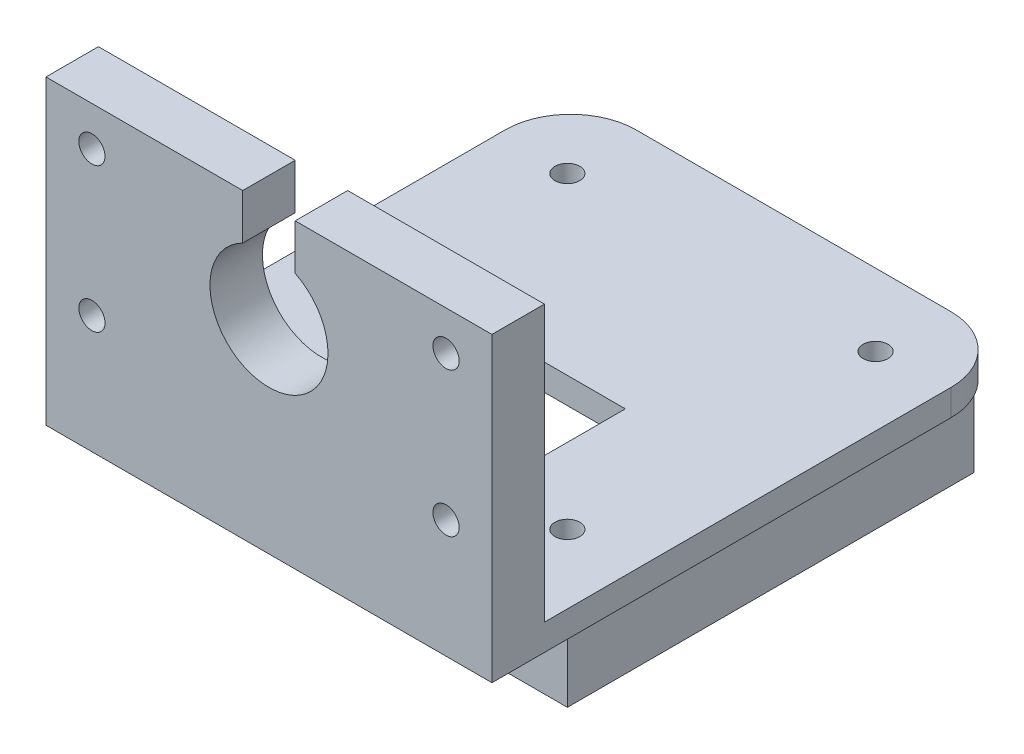
SolidWorks part; units mm, degrees
ref_plane "Спереди" through (0, 0, 0) normal (0, 0, 1) x (1, 0, 0)
ref_plane "Сверху" through (0, 0, 0) normal (0, 1, 0) x (1, 0, 0)
ref_plane "Справа" through (0, 0, 0) normal (1, 0, 0) x (0, 0, -1)
sketch "Эскиз1" plane through (0, 0, 0) normal (0, 0, 1) x (1, 0, 0)
  line L0 (0, 11.5) -> (0, 8.5) construction
  line L1 (-17, -11.5) -> (17, -11.5)
  line L2 (-17, -11.5) -> (-17, 11.5)
  line L4 (17, -11.5) -> (17, 11.5)
  line L5 (-17, -11.5) -> (17, 11.5) construction
  line L6 (-17, 11.5) -> (17, -11.5) construction
  line L7 (-13.5, 8.5) -> (13.5, 8.5) construction
  line L8 (-13.5, 8.5) -> (-13.5, -2.5) construction
  line L9 (-13.5, -2.5) -> (13.5, -2.5) construction
  line L10 (13.5, -2.5) -> (13.5, -9.5) construction
  line L11 (-17, -9.5) -> (17, -9.5) construction
  line L12 (0, -9.5) -> (0, -0.5) construction
  line L13 (-2, 11.5) -> (2, 11.5) construction
  line L14 (-2, 11.5) -> (-2, 8.0311)
  line L15 (2, 11.5) -> (2, 8.0311)
  line L16 (2, 11.5) -> (17, 11.5)
  line L17 (-2, 11.5) -> (-17, 11.5)
  circle A0 centre (-13.5, 8.5) radius 1
  circle A1 centre (13.5, 8.5) radius 1
  circle A2 centre (-13.5, -2.5) radius 1
  circle A3 centre (13.5, -2.5) radius 1
  arc A5 (-2, 8.0311) -> (2, 8.0311) centre (0, 4) ccw
  point P0 (0, 0)
  point P11 (0, 8.5)
  point P27 (0, 11.5)
extrude "Бобышка-Вытянуть1" add sketch "Эскиз1" along normal blind 4
sketch "Эскиз2" plane through (0, 0, 0) normal (0, 0, -1) x (-1, 0, 0)
  line L1 (-17, -9.5) -> (17, -9.5)
  line L2 (-17, -9.5) -> (-17, -11.5)
  line L3 (-17, -11.5) -> (17, -11.5)
  line L4 (17, -9.5) -> (17, -11.5)
  line L5 (-17, -9.5) -> (17, -11.5) construction
  line L6 (-17, -11.5) -> (17, -9.5) construction
  point P4 (0, -10.5)
extrude "Бобышка-Вытянуть2" add sketch "Эскиз2" along normal blind 36
sketch "Эскиз3" plane through (0, -11.5, 0) normal (0, -1, 0) x (1, 0, 0)
  line L1 (0, -18.75) -> (0, 0) construction
  line L3 (6, -17.1698) -> (-6, -17.1698)
  line L5 (6, -17.1698) -> (6, -3)
  line L6 (0, -18.75) -> (0, -36) construction
  line L7 (6, -3) -> (-6, -3)
  line L8 (-11.75, -7) -> (11.75, -7) construction
  line L9 (-11.75, -7) -> (-11.75, -30.5) construction
  line L10 (-11.75, -30.5) -> (11.75, -30.5) construction
  line L11 (11.75, -7) -> (11.75, -30.5) construction
  line L12 (-11.75, -7) -> (11.75, -30.5) construction
  line L13 (-11.75, -30.5) -> (11.75, -7) construction
  line L14 (-6, -3) -> (-6, -17.1698)
  line L15 (0, -3) -> (0, 0) construction
  line L16 (-17, 0) -> (17, 0) construction
  line L17 (17, -36) -> (-17, -36) construction
  line L18 (0, -18.75) -> (-17, -18.75) construction
  line L19 (-17, 4) -> (-17, -36) construction
  line L20 (0, -18.75) -> (17, -18.75) construction
  line L21 (17, 4) -> (17, -36) construction
  circle A0 centre (11.75, -7) radius 0.95
  circle A1 centre (11.75, -30.5) radius 0.95
  circle A2 centre (-11.75, -30.5) radius 0.95
  circle A3 centre (-11.75, -7) radius 0.95
  point P5 (0, 0)
  point P10 (0, -18.75)
  point P12 (0, -18.75)
extrude "Вырез-Вытянуть1" cut sketch "Эскиз3" against normal blind 3
sketch "Эскиз4" plane through (0, -11.5, 0) normal (0, -1, 0) x (1, 0, 0)
  circle A0 centre (11.75, -7) radius 2.2
  circle A1 centre (11.75, -30.5) radius 2.2
  circle A2 centre (-11.75, -7) radius 2.2
  circle A3 centre (-11.75, -30.5) radius 2.2
  circle A4 centre (11.75, -7) radius 0.95
  circle A5 centre (11.75, -30.5) radius 0.95
  circle A6 centre (-11.75, -30.5) radius 0.95
  circle A7 centre (-11.75, -7) radius 0.95
extrude "Бобышка-Вытянуть3" add sketch "Эскиз4" along normal blind 2
fillet "Скругление1" radius 5 2 edges at (17, -10.5, -36) (-17, -10.5, -36)
sketch "Эскиз5" plane through (0, -11.5, 0) normal (0, -1, 0) x (1, 0, 0)
  line L0 (-11.75, -7) -> (11.75, -30.5) construction
  line L1 (11.75, -7) -> (-11.75, -30.5) construction
  line L2 (-6, -3.25) -> (6, -3.25) construction
  line L3 (-14, -32.75) -> (14, -32.75)
  line L4 (-14, -32.75) -> (-14, -4.75)
  line L6 (14, -32.75) -> (14, -4.75)
  line L7 (-14, -32.75) -> (14, -4.75) construction
  line L8 (-14, -4.75) -> (14, -32.75) construction
  line L10 (-15.5, -3.25) -> (-15.5, -34.25)
  line L11 (-15.5, -34.25) -> (15.5, -34.25)
  line L12 (15.5, -3.25) -> (15.5, -34.25)
  line L13 (-15.5, -3.25) -> (15.5, -34.25) construction
  line L14 (-15.5, -34.25) -> (15.5, -3.25) construction
  line L15 (-15.5, -4.75) -> (-15.5, -34.25)
  line L16 (-14, -4.75) -> (-6, -4.75)
  line L17 (15.5, -4.75) -> (15.5, -34.25)
  line L18 (-6, -3) -> (-6, -17.1698) construction
  line L19 (-6, -4.75) -> (-6, -3.25)
  line L20 (6, -3.25) -> (6, -4.75)
  line L21 (6, -17.1698) -> (6, -3) construction
  line L22 (6, -4.75) -> (14, -4.75)
  line L23 (-15.5, -3.25) -> (-6, -3.25)
  line L24 (6, -3.25) -> (15.5, -3.25)
  point P8 (0, -18.75)
  point P13 (0, -18.75)
  point P23 (0, -3.25)
extrude "Бобышка-Вытянуть5" add sketch "Эскиз5" along normal blind 6
